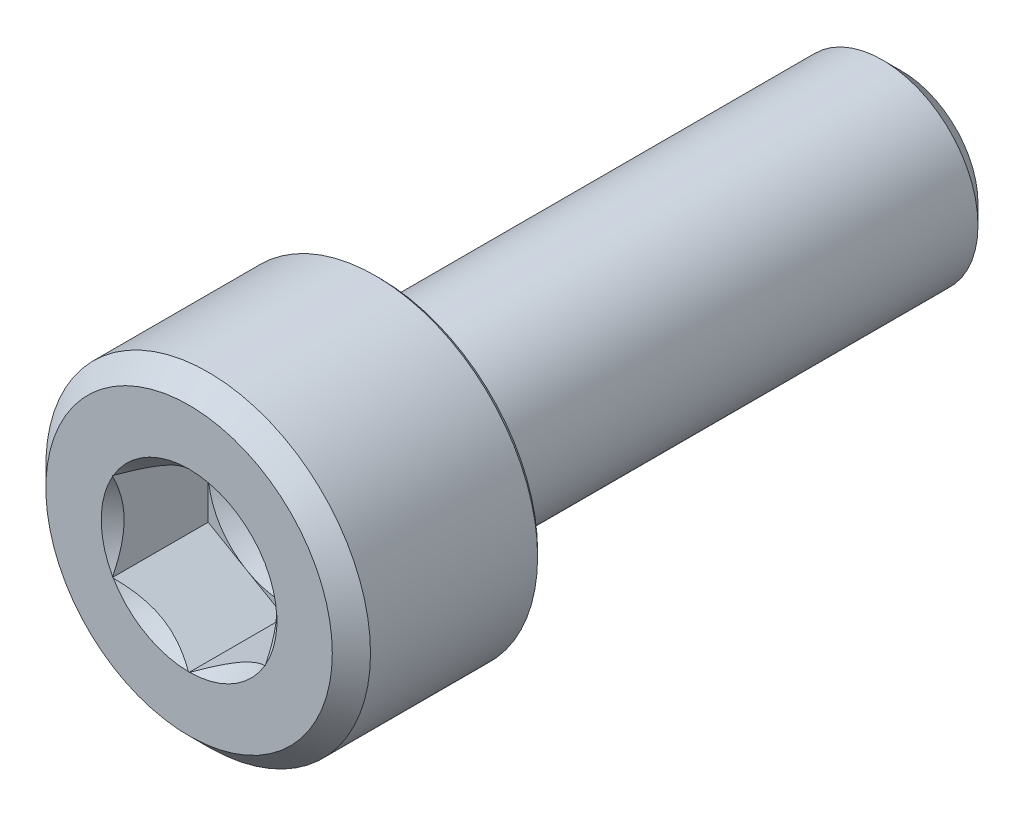
SolidWorks part; units mm, degrees
ref_plane "Alzado" through (0, 0, 0) normal (0, 0, 1) x (1, 0, 0)
ref_plane "Planta" through (0, 0, 0) normal (0, 1, 0) x (1, 0, 0)
ref_plane "Vista lateral" through (0, 0, 0) normal (1, 0, 0) x (0, 0, -1)
sketch "Croquis1" plane through (0, 0, 0) normal (1, 0, 0) x (0, 0, -1)
  line L0 (0, 0) -> (15, 0)
  line L1 (15, 0) -> (15, 2)
  line L2 (14.5, 2.5) -> (1.9453, 2.5)
  line L3 (1.3453, 2.542) -> (1.3453, 4.125)
  line L4 (1.2203, 4.25) -> (-3.1547, 4.25)
  line L5 (-3.6547, 3.75) -> (-3.6547, 2.3)
  line L7 (-3.3547, 2) -> (-1.1547, 2)
  line L8 (-1.1547, 2) -> (0, 0)
  line L9 (15, 2) -> (14.5, 2.5)
  line L10 (-3.1547, 4.25) -> (-3.6547, 3.75)
  line L11 (-3.6547, 2.3) -> (-3.3547, 2)
  line L12 (1.3453, 4.125) -> (1.2203, 4.25)
  line L13 (1.9453, 2.5) -> (1.3453, 2.542)
  point P3 (15, 2.5)
  point P5 (1.3453, 2.5)
  point P6 (1.3453, 4.25)
  point P7 (-3.6547, 4.25)
  point P8 (-3.6547, 2)
  point P10 (0, 0)
  dimension "D1" = 15
  dimension "D2" = 2.5
  dimension "D3" = 4.25
  dimension "D4" = 0.3
  dimension "D5" = 60
  dimension "D6" = 5
  dimension "D7" = 0.5
  dimension "D8" = 45
  dimension "D9" = 0.5
  dimension "D10" = 45
  dimension "D11" = 45
  dimension "D12" = 0.125
  dimension "D13" = 45
  dimension "D14" = 0.6
  dimension "D15" = 4
  dimension "D16" = 2.5
revolve "Revolución1" add sketch "Croquis1" angle 360 about L0
sketch "Croquis2" plane through (0, 0, 3.6547) normal (0, 0, 1) x (1, 0, 0)
  line L1 (0, 2.3094) -> (-2, 1.1547)
  line L2 (-2, 1.1547) -> (-2, -1.1547)
  line L3 (-2, -1.1547) -> (0, -2.3094)
  line L4 (0, -2.3094) -> (2, -1.1547)
  line L5 (2, -1.1547) -> (2, 1.1547)
  line L6 (2, 1.1547) -> (0, 2.3094)
  circle A0 centre (0, 0) radius 2 construction
  dimension "D1" = 4
extrude "Cortar-Extruir1" cut sketch "Croquis2" against normal blind 2.5
